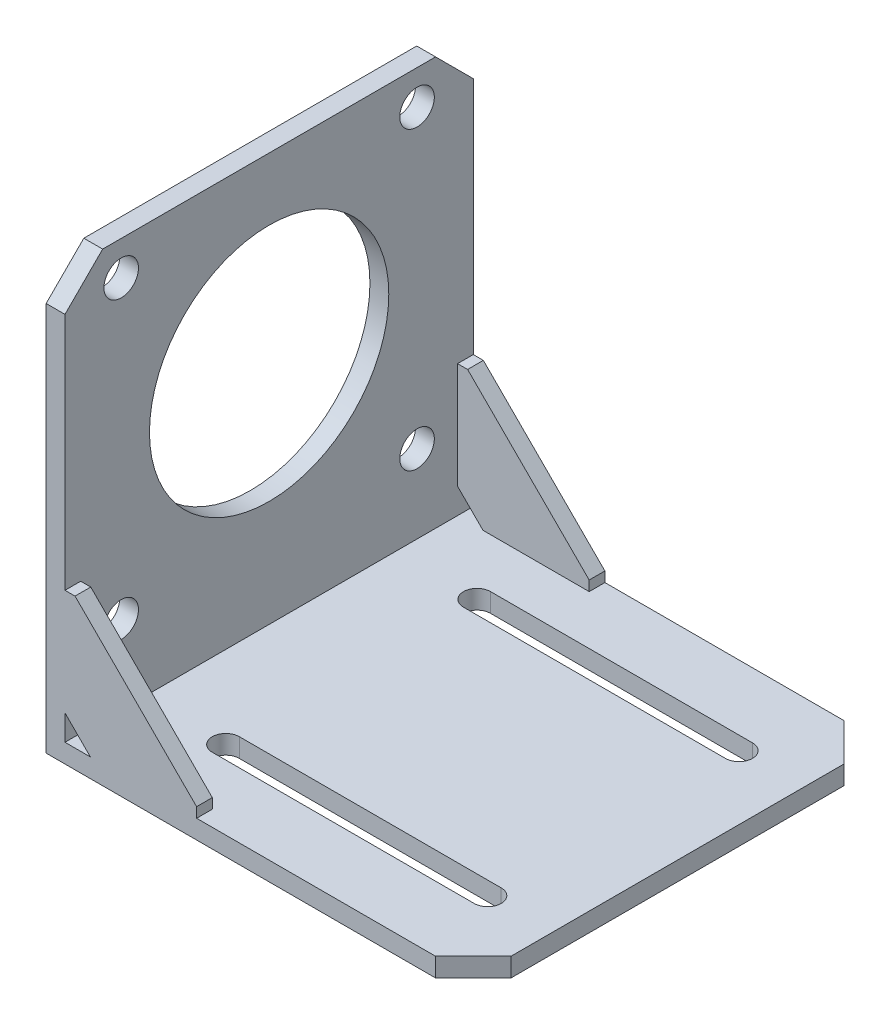
SolidWorks part; units mm, degrees
ref_plane "Front Plane" through (0, 0, 0) normal (0, 0, 1) x (1, 0, 0)
ref_plane "Top Plane" through (0, 0, 0) normal (0, 1, 0) x (1, 0, 0)
ref_plane "Right Plane" through (0, 0, 0) normal (1, 0, 0) x (0, 0, -1)
sketch "Sketch1" plane through (0, 0, 0) normal (0, 0, 1) x (1, 0, 0)
  line L0 (0, 0) -> (0, 68)
  line L1 (0, 68) -> (3, 68)
  line L2 (3, 68) -> (3, 3)
  line L3 (3, 3) -> (68, 3)
  line L4 (68, 3) -> (68, 0)
  line L5 (68, 0) -> (0, 0)
  dimension "D1" = 3
  dimension "D2" = 3
  dimension "D3" = 65
  dimension "D4" = 65
extrude "Boss-Extrude1" add sketch "Sketch1" along normal blind 65
chamfer "Chamfer1" distance 6 angle 45 4 edges at (68, 1.5, 65) (68, 1.5, 0) (1.5, 68, 0) (1.5, 68, 65)
sketch "Sketch2" plane through (0, 0, 65) normal (0, 0, 1) x (1, 0, 0)
  line L0 (4.6002, 23.9559) -> (23.9559, 4.6002)
  line L3 (23.9559, 3) -> (7.0478, 3)
  line L4 (3, 7.0478) -> (3, 23.9559)
  line L5 (4.6002, 23.9559) -> (3, 23.9559)
  line L6 (23.9559, 4.6002) -> (23.9559, 3)
  line L7 (3, 7.0478) -> (7.0478, 3)
  dimension "D1" = 45
extrude "Boss-Extrude2" add sketch "Sketch2" against normal blind 2.5
ref_plane "Plane1" through (0, 0, 32.5) normal (0, 0, 1) x (1, 0, 0)
mirror "Mirror1" about plane through (0, 0, 32.5) normal (0, 0, 1) of "Boss-Extrude2"
sketch "Sketch3" plane through (0, 0, 0) normal (-1, 0, 0) x (0, 0, 1)
  line L0 (59, 68) -> (6, 68) construction
  circle A0 centre (32.5, 39) radius 19.05
  circle A1 centre (8.95, 62.55) radius 2.75
  circle A2 centre (56.05, 62.55) radius 2.75
  circle A3 centre (8.95, 15.45) radius 2.75
  circle A4 centre (56.05, 15.45) radius 2.75
  dimension "D2" = 38.1
  dimension "D3" = 5.5
  dimension "D4" = 47.1
  dimension "D5" = 47.1
  dimension "D6" = 47.1
  dimension "D8" = 23.55
  dimension "D1" = 29
  dimension "D7" = 23.55
extrude "Cut-Extrude1" cut sketch "Sketch3" against normal blind 3
sketch "Sketch4" plane through (0, 0, 0) normal (0, -1, 0) x (1, 0, 0)
  line L0 (16.1, 52.5) -> (57.8, 52.5) construction
  line L1 (16.1, 54.65) -> (57.8, 54.65)
  line L2 (16.1, 50.35) -> (57.8, 50.35)
  line L3 (16.1, 12.5) -> (57.8, 12.5) construction
  line L4 (16.1, 14.65) -> (57.8, 14.65)
  line L5 (16.1, 10.35) -> (57.8, 10.35)
  line L6 (0, 65) -> (62, 65) construction
  line L7 (68, 32.5) -> (0, 32.5) construction
  line L8 (68, 59) -> (68, 6) construction
  line L9 (0, 65) -> (0, 0) construction
  arc A0 (16.1, 54.65) -> (16.1, 50.35) centre (16.1, 52.5) ccw
  arc A1 (57.8, 50.35) -> (57.8, 54.65) centre (57.8, 52.5) ccw
  arc A2 (16.1, 14.65) -> (16.1, 10.35) centre (16.1, 12.5) ccw
  arc A3 (57.8, 10.35) -> (57.8, 14.65) centre (57.8, 12.5) ccw
  point P2 (36.95, 52.5)
  point P7 (36.95, 12.5)
  dimension "D1" = 4.3
  dimension "D2" = 41.7
  dimension "D3" = 40
  dimension "D4" = 12.5
  dimension "D5" = 10.2
extrude "Cut-Extrude2" cut sketch "Sketch4" against normal blind 3
